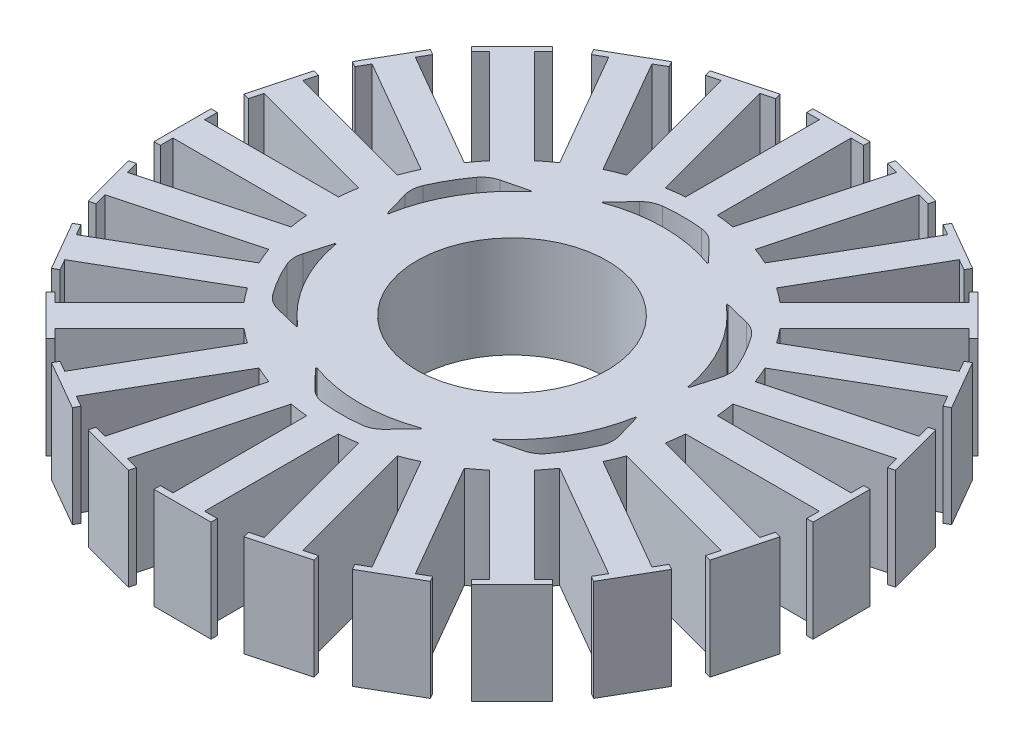
SolidWorks part; units mm, degrees
ref_plane "Front Plane" through (0, 0, 0) normal (0, 0, 1) x (1, 0, 0)
ref_plane "Top Plane" through (0, 0, 0) normal (0, 1, 0) x (1, 0, 0)
ref_plane "Right Plane" through (0, 0, 0) normal (1, 0, 0) x (0, 0, -1)
sketch "Sketch3" plane through (0, 0, 0) normal (0, 1, 0) x (1, 0, 0)
  line L0 (0, 0) -> (0, 19.6595) construction
  line L1 (-1.25, 25.5) -> (-1.25, 14.9478)
  line L2 (-1.25, 25.5) -> (-2.25, 25.5)
  line L3 (-2.25, 25.5) -> (-2.25, 26)
  line L4 (-2.25, 26) -> (2.25, 26)
  line L5 (2.25, 26) -> (2.25, 25.5)
  line L6 (2.25, 25.5) -> (1.25, 25.5)
  line L7 (1.25, 25.5) -> (1.25, 14.9478)
  line L8 (5.3925, 24.9546) -> (2.6614, 14.762)
  line L9 (7.8073, 24.3076) -> (5.0762, 14.115)
  line L10 (8.7732, 24.0488) -> (7.8073, 24.3076)
  line L11 (4.556, 25.6964) -> (8.9026, 24.5317)
  line L12 (5.3925, 24.9546) -> (4.4266, 25.2135)
  line L13 (4.4266, 25.2135) -> (4.556, 25.6964)
  line L14 (8.9026, 24.5317) -> (8.7732, 24.0488)
  line L15 (11.6675, 22.7086) -> (6.3914, 13.5702)
  line L16 (13.8325, 21.4586) -> (8.5564, 12.3202)
  line L17 (14.6986, 20.9586) -> (13.8325, 21.4586)
  line L18 (11.0514, 23.6417) -> (14.9486, 21.3917)
  line L19 (11.6675, 22.7086) -> (10.8014, 23.2086)
  line L20 (10.8014, 23.2086) -> (11.0514, 23.6417)
  line L21 (14.9486, 21.3917) -> (14.6986, 20.9586)
  line L22 (17.1473, 18.9151) -> (9.6858, 11.4536)
  line L23 (18.9151, 17.1473) -> (11.4536, 9.6858)
  line L24 (19.6222, 16.4402) -> (18.9151, 17.1473)
  line L25 (16.7938, 19.9758) -> (19.9758, 16.7938)
  line L26 (17.1473, 18.9151) -> (16.4402, 19.6222)
  line L27 (16.4402, 19.6222) -> (16.7938, 19.9758)
  line L28 (19.9758, 16.7938) -> (19.6222, 16.4402)
  line L29 (21.4586, 13.8325) -> (12.3202, 8.5564)
  line L30 (22.7086, 11.6675) -> (13.5702, 6.3914)
  line L31 (23.2086, 10.8014) -> (22.7086, 11.6675)
  line L32 (21.3917, 14.9486) -> (23.6417, 11.0514)
  line L33 (21.4586, 13.8325) -> (20.9586, 14.6986)
  line L34 (20.9586, 14.6986) -> (21.3917, 14.9486)
  line L35 (23.6417, 11.0514) -> (23.2086, 10.8014)
  line L36 (24.3076, 7.8073) -> (14.115, 5.0762)
  line L37 (24.9546, 5.3925) -> (14.762, 2.6614)
  line L38 (25.2135, 4.4266) -> (24.9546, 5.3925)
  line L39 (24.5317, 8.9026) -> (25.6964, 4.556)
  line L40 (24.3076, 7.8073) -> (24.0488, 8.7732)
  line L41 (24.0488, 8.7732) -> (24.5317, 8.9026)
  line L42 (25.6964, 4.556) -> (25.2135, 4.4266)
  line L43 (25.5, 1.25) -> (14.9478, 1.25)
  line L44 (25.5, -1.25) -> (14.9478, -1.25)
  line L45 (25.5, -2.25) -> (25.5, -1.25)
  line L46 (26, 2.25) -> (26, -2.25)
  line L47 (25.5, 1.25) -> (25.5, 2.25)
  line L48 (25.5, 2.25) -> (26, 2.25)
  line L49 (26, -2.25) -> (25.5, -2.25)
  line L50 (24.9546, -5.3925) -> (14.762, -2.6614)
  line L51 (24.3076, -7.8073) -> (14.115, -5.0762)
  line L52 (24.0488, -8.7732) -> (24.3076, -7.8073)
  line L53 (25.6964, -4.556) -> (24.5317, -8.9026)
  line L54 (24.9546, -5.3925) -> (25.2135, -4.4266)
  line L55 (25.2135, -4.4266) -> (25.6964, -4.556)
  line L56 (24.5317, -8.9026) -> (24.0488, -8.7732)
  line L57 (22.7086, -11.6675) -> (13.5702, -6.3914)
  line L58 (21.4586, -13.8325) -> (12.3202, -8.5564)
  line L59 (20.9586, -14.6986) -> (21.4586, -13.8325)
  line L60 (23.6417, -11.0514) -> (21.3917, -14.9486)
  line L61 (22.7086, -11.6675) -> (23.2086, -10.8014)
  line L62 (23.2086, -10.8014) -> (23.6417, -11.0514)
  line L63 (21.3917, -14.9486) -> (20.9586, -14.6986)
  line L64 (18.9151, -17.1473) -> (11.4536, -9.6858)
  line L65 (17.1473, -18.9151) -> (9.6858, -11.4536)
  line L66 (16.4402, -19.6222) -> (17.1473, -18.9151)
  line L67 (19.9758, -16.7938) -> (16.7938, -19.9758)
  line L68 (18.9151, -17.1473) -> (19.6222, -16.4402)
  line L69 (19.6222, -16.4402) -> (19.9758, -16.7938)
  line L70 (16.7938, -19.9758) -> (16.4402, -19.6222)
  line L71 (13.8325, -21.4586) -> (8.5564, -12.3202)
  line L72 (11.6675, -22.7086) -> (6.3914, -13.5702)
  line L73 (10.8014, -23.2086) -> (11.6675, -22.7086)
  line L74 (14.9486, -21.3917) -> (11.0514, -23.6417)
  line L75 (13.8325, -21.4586) -> (14.6986, -20.9586)
  line L76 (14.6986, -20.9586) -> (14.9486, -21.3917)
  line L77 (11.0514, -23.6417) -> (10.8014, -23.2086)
  line L78 (7.8073, -24.3076) -> (5.0762, -14.115)
  line L79 (5.3925, -24.9546) -> (2.6614, -14.762)
  line L80 (4.4266, -25.2135) -> (5.3925, -24.9546)
  line L81 (8.9026, -24.5317) -> (4.556, -25.6964)
  line L82 (7.8073, -24.3076) -> (8.7732, -24.0488)
  line L83 (8.7732, -24.0488) -> (8.9026, -24.5317)
  line L84 (4.556, -25.6964) -> (4.4266, -25.2135)
  line L85 (1.25, -25.5) -> (1.25, -14.9478)
  line L86 (-1.25, -25.5) -> (-1.25, -14.9478)
  line L87 (-2.25, -25.5) -> (-1.25, -25.5)
  line L88 (2.25, -26) -> (-2.25, -26)
  line L89 (1.25, -25.5) -> (2.25, -25.5)
  line L90 (2.25, -25.5) -> (2.25, -26)
  line L91 (-2.25, -26) -> (-2.25, -25.5)
  line L92 (-5.3925, -24.9546) -> (-2.6614, -14.762)
  line L93 (-7.8073, -24.3076) -> (-5.0762, -14.115)
  line L94 (-8.7732, -24.0488) -> (-7.8073, -24.3076)
  line L95 (-4.556, -25.6964) -> (-8.9026, -24.5317)
  line L96 (-5.3925, -24.9546) -> (-4.4266, -25.2135)
  line L97 (-4.4266, -25.2135) -> (-4.556, -25.6964)
  line L98 (-8.9026, -24.5317) -> (-8.7732, -24.0488)
  line L99 (-11.6675, -22.7086) -> (-6.3914, -13.5702)
  line L100 (-13.8325, -21.4586) -> (-8.5564, -12.3202)
  line L101 (-14.6986, -20.9586) -> (-13.8325, -21.4586)
  line L102 (-11.0514, -23.6417) -> (-14.9486, -21.3917)
  line L103 (-11.6675, -22.7086) -> (-10.8014, -23.2086)
  line L104 (-10.8014, -23.2086) -> (-11.0514, -23.6417)
  line L105 (-14.9486, -21.3917) -> (-14.6986, -20.9586)
  line L106 (-17.1473, -18.9151) -> (-9.6858, -11.4536)
  line L107 (-18.9151, -17.1473) -> (-11.4536, -9.6858)
  line L108 (-19.6222, -16.4402) -> (-18.9151, -17.1473)
  line L109 (-16.7938, -19.9758) -> (-19.9758, -16.7938)
  line L110 (-17.1473, -18.9151) -> (-16.4402, -19.6222)
  line L111 (-16.4402, -19.6222) -> (-16.7938, -19.9758)
  line L112 (-19.9758, -16.7938) -> (-19.6222, -16.4402)
  line L113 (-21.4586, -13.8325) -> (-12.3202, -8.5564)
  line L114 (-22.7086, -11.6675) -> (-13.5702, -6.3914)
  line L115 (-23.2086, -10.8014) -> (-22.7086, -11.6675)
  line L116 (-21.3917, -14.9486) -> (-23.6417, -11.0514)
  line L117 (-21.4586, -13.8325) -> (-20.9586, -14.6986)
  line L118 (-20.9586, -14.6986) -> (-21.3917, -14.9486)
  line L119 (-23.6417, -11.0514) -> (-23.2086, -10.8014)
  line L120 (-24.3076, -7.8073) -> (-14.115, -5.0762)
  line L121 (-24.9546, -5.3925) -> (-14.762, -2.6614)
  line L122 (-25.2135, -4.4266) -> (-24.9546, -5.3925)
  line L123 (-24.5317, -8.9026) -> (-25.6964, -4.556)
  line L124 (-24.3076, -7.8073) -> (-24.0488, -8.7732)
  line L125 (-24.0488, -8.7732) -> (-24.5317, -8.9026)
  line L126 (-25.6964, -4.556) -> (-25.2135, -4.4266)
  line L127 (-25.5, -1.25) -> (-14.9478, -1.25)
  line L128 (-25.5, 1.25) -> (-14.9478, 1.25)
  line L129 (-25.5, 2.25) -> (-25.5, 1.25)
  line L130 (-26, -2.25) -> (-26, 2.25)
  line L131 (-25.5, -1.25) -> (-25.5, -2.25)
  line L132 (-25.5, -2.25) -> (-26, -2.25)
  line L133 (-26, 2.25) -> (-25.5, 2.25)
  line L134 (-24.9546, 5.3925) -> (-14.762, 2.6614)
  line L135 (-24.3076, 7.8073) -> (-14.115, 5.0762)
  line L136 (-24.0488, 8.7732) -> (-24.3076, 7.8073)
  line L137 (-25.6964, 4.556) -> (-24.5317, 8.9026)
  line L138 (-24.9546, 5.3925) -> (-25.2135, 4.4266)
  line L139 (-25.2135, 4.4266) -> (-25.6964, 4.556)
  line L140 (-24.5317, 8.9026) -> (-24.0488, 8.7732)
  line L141 (-22.7086, 11.6675) -> (-13.5702, 6.3914)
  line L142 (-21.4586, 13.8325) -> (-12.3202, 8.5564)
  line L143 (-20.9586, 14.6986) -> (-21.4586, 13.8325)
  line L144 (-23.6417, 11.0514) -> (-21.3917, 14.9486)
  line L145 (-22.7086, 11.6675) -> (-23.2086, 10.8014)
  line L146 (-23.2086, 10.8014) -> (-23.6417, 11.0514)
  line L147 (-21.3917, 14.9486) -> (-20.9586, 14.6986)
  line L148 (-18.9151, 17.1473) -> (-11.4536, 9.6858)
  line L149 (-17.1473, 18.9151) -> (-9.6858, 11.4536)
  line L150 (-16.4402, 19.6222) -> (-17.1473, 18.9151)
  line L151 (-19.9758, 16.7938) -> (-16.7938, 19.9758)
  line L152 (-18.9151, 17.1473) -> (-19.6222, 16.4402)
  line L153 (-19.6222, 16.4402) -> (-19.9758, 16.7938)
  line L154 (-16.7938, 19.9758) -> (-16.4402, 19.6222)
  line L155 (-13.8325, 21.4586) -> (-8.5564, 12.3202)
  line L156 (-11.6675, 22.7086) -> (-6.3914, 13.5702)
  line L157 (-10.8014, 23.2086) -> (-11.6675, 22.7086)
  line L158 (-14.9486, 21.3917) -> (-11.0514, 23.6417)
  line L159 (-13.8325, 21.4586) -> (-14.6986, 20.9586)
  line L160 (-14.6986, 20.9586) -> (-14.9486, 21.3917)
  line L161 (-11.0514, 23.6417) -> (-10.8014, 23.2086)
  line L162 (-7.8073, 24.3076) -> (-5.0762, 14.115)
  line L163 (-5.3925, 24.9546) -> (-2.6614, 14.762)
  line L164 (-4.4266, 25.2135) -> (-5.3925, 24.9546)
  line L165 (-8.9026, 24.5317) -> (-4.556, 25.6964)
  line L166 (-7.8073, 24.3076) -> (-8.7732, 24.0488)
  line L167 (-8.7732, 24.0488) -> (-8.9026, 24.5317)
  line L168 (-4.556, 25.6964) -> (-4.4266, 25.2135)
  circle A0 centre (0, 0) radius 7.5
  arc A1 (-14.762, 2.6614) -> (-14.9478, 1.25) centre (0, 0) ccw
  arc A2 (-13.5702, 6.3914) -> (-14.115, 5.0762) centre (0, 0) ccw
  arc A3 (-11.4536, 9.6858) -> (-12.3202, 8.5564) centre (0, 0) ccw
  arc A4 (-8.5564, 12.3202) -> (-9.6858, 11.4536) centre (0, 0) ccw
  arc A5 (-5.0762, 14.115) -> (-6.3914, 13.5702) centre (0, 0) ccw
  arc A6 (-1.25, 14.9478) -> (-2.6614, 14.762) centre (0, 0) ccw
  arc A7 (2.6614, 14.762) -> (1.25, 14.9478) centre (0, 0) ccw
  arc A8 (6.3914, 13.5702) -> (5.0762, 14.115) centre (0, 0) ccw
  arc A9 (9.6858, 11.4536) -> (8.5564, 12.3202) centre (0, 0) ccw
  arc A10 (12.3202, 8.5564) -> (11.4536, 9.6858) centre (0, 0) ccw
  arc A11 (14.115, 5.0762) -> (13.5702, 6.3914) centre (0, 0) ccw
  arc A12 (14.9478, 1.25) -> (14.762, 2.6614) centre (0, 0) ccw
  arc A13 (14.762, -2.6614) -> (14.9478, -1.25) centre (0, 0) ccw
  arc A14 (13.5702, -6.3914) -> (14.115, -5.0762) centre (0, 0) ccw
  arc A15 (11.4536, -9.6858) -> (12.3202, -8.5564) centre (0, 0) ccw
  arc A16 (8.5564, -12.3202) -> (9.6858, -11.4536) centre (0, 0) ccw
  arc A17 (5.0762, -14.115) -> (6.3914, -13.5702) centre (0, 0) ccw
  arc A18 (1.25, -14.9478) -> (2.6614, -14.762) centre (0, 0) ccw
  arc A19 (-2.6614, -14.762) -> (-1.25, -14.9478) centre (0, 0) ccw
  arc A20 (-6.3914, -13.5702) -> (-5.0762, -14.115) centre (0, 0) ccw
  arc A21 (-9.6858, -11.4536) -> (-8.5564, -12.3202) centre (0, 0) ccw
  arc A22 (-12.3202, -8.5564) -> (-11.4536, -9.6858) centre (0, 0) ccw
  arc A23 (-14.115, -5.0762) -> (-13.5702, -6.3914) centre (0, 0) ccw
  arc A24 (-14.9478, -1.25) -> (-14.762, -2.6614) centre (0, 0) ccw
  point P9 (0, 26)
  point P201 (0, 0)
  dimension "D1" = 15
  dimension "D3" = 30
  dimension "D2" = 4.5
  dimension "D4" = 0.5
  dimension "D5" = 0.5
  dimension "D6" = 2.5
  dimension "D7" = 26
  dimension "D8" = 24
extrude "Boss-Extrude1" add sketch "Sketch3" along normal blind 8
sketch "Sketch4" plane through (0, 8, 0) normal (0, 1, 0) x (1, 0, 0)
  line L0 (-2.6614, 14.762) -> (-1.0542, 8.764) construction
  line L1 (2.6614, 14.762) -> (4.7776, 22.6598) construction
  line L2 (2.7481, 12.8126) -> (4.1439, 11.3629)
  line L3 (-5.0762, 14.115) -> (-6.077, 17.8501) construction
  line L4 (9.722, 8.7862) -> (7.7686, 9.2702)
  line L5 (5.0762, 14.115) -> (6.0658, 17.8082) construction
  line L6 (12.4701, 4.0263) -> (11.9125, 2.0927)
  line L7 (-2.7481, 12.8126) -> (-4.1439, 11.3629)
  line L8 (12.4701, -4.0263) -> (11.9125, -2.0927)
  line L9 (9.722, -8.7862) -> (7.7686, -9.2702)
  line L10 (2.7481, -12.8126) -> (4.1439, -11.3629)
  line L11 (-2.7481, -12.8126) -> (-4.1439, -11.3629)
  line L12 (-9.722, -8.7862) -> (-7.7686, -9.2702)
  line L13 (-12.4701, -4.0263) -> (-11.9125, -2.0927)
  line L14 (-12.4701, 4.0263) -> (-11.9125, 2.0927)
  line L15 (-9.722, 8.7862) -> (-7.7686, 9.2702)
  arc A0 (-4.6865, -12.6605) -> (4.6865, -12.6605) centre (0, 0) ccw construction
  arc A1 (-8.5564, 12.3202) -> (-9.6858, 11.4536) centre (0, 0) ccw construction
  arc A2 (-4.2963, -11.2045) -> (4.2963, -11.2045) centre (0, 0) ccw construction
  circle A3 centre (0, 0) radius 13.5 construction
  circle A4 centre (0, 0) radius 12 construction
  arc A5 (4.0908, 11.2812) -> (-4.0908, 11.2812) centre (0, 0) ccw
  arc A6 (1.5347, 13.4125) -> (-1.5347, 13.4125) centre (0, 0) ccw
  arc A7 (-1.5347, 13.4125) -> (-2.7481, 12.8126) centre (-1.3074, 11.4254) ccw
  arc A8 (1.5347, 13.4125) -> (2.7481, 12.8126) centre (1.3074, 11.4254) cw
  arc A9 (4.1439, 11.3629) -> (4.0908, 11.2812) centre (4.1079, 11.3282) cw
  arc A10 (-4.0908, 11.2812) -> (-4.1439, 11.3629) centre (-4.1079, 11.3282) cw
  arc A11 (7.7244, 9.1834) -> (7.7686, 9.2702) centre (7.7566, 9.2216) cw
  arc A12 (10.8482, 8.0354) -> (9.722, 8.7862) centre (9.241, 6.8449) ccw
  arc A13 (11.8152, 2.0978) -> (7.7244, 9.1834) centre (0, 0) ccw
  arc A14 (11.9125, 2.0927) -> (11.8152, 2.0978) centre (11.8644, 2.1066) cw
  arc A15 (12.3829, 5.3771) -> (12.4701, 4.0263) centre (10.5484, 4.5805) cw
  arc A16 (12.3829, 5.3771) -> (10.8482, 8.0354) centre (0, 0) ccw
  arc A17 (11.8152, -2.0978) -> (11.9125, -2.0927) centre (11.8644, -2.1066) cw
  arc A18 (12.3829, -5.3771) -> (12.4701, -4.0263) centre (10.5484, -4.5805) ccw
  arc A19 (7.7244, -9.1834) -> (11.8152, -2.0978) centre (0, 0) ccw
  arc A20 (7.7686, -9.2702) -> (7.7244, -9.1834) centre (7.7566, -9.2216) cw
  arc A21 (10.8482, -8.0354) -> (9.722, -8.7862) centre (9.241, -6.8449) cw
  arc A22 (10.8482, -8.0354) -> (12.3829, -5.3771) centre (0, 0) ccw
  arc A23 (4.0908, -11.2812) -> (4.1439, -11.3629) centre (4.1079, -11.3282) cw
  arc A24 (1.5347, -13.4125) -> (2.7481, -12.8126) centre (1.3074, -11.4254) ccw
  arc A25 (-4.0908, -11.2812) -> (4.0908, -11.2812) centre (0, 0) ccw
  arc A26 (-4.1439, -11.3629) -> (-4.0908, -11.2812) centre (-4.1079, -11.3282) cw
  arc A27 (-1.5347, -13.4125) -> (-2.7481, -12.8126) centre (-1.3074, -11.4254) cw
  arc A28 (-1.5347, -13.4125) -> (1.5347, -13.4125) centre (0, 0) ccw
  arc A29 (-7.7244, -9.1834) -> (-7.7686, -9.2702) centre (-7.7566, -9.2216) cw
  arc A30 (-10.8482, -8.0354) -> (-9.722, -8.7862) centre (-9.241, -6.8449) ccw
  arc A31 (-11.8152, -2.0978) -> (-7.7244, -9.1834) centre (0, 0) ccw
  arc A32 (-11.9125, -2.0927) -> (-11.8152, -2.0978) centre (-11.8644, -2.1066) cw
  arc A33 (-12.3829, -5.3771) -> (-12.4701, -4.0263) centre (-10.5484, -4.5805) cw
  arc A34 (-12.3829, -5.3771) -> (-10.8482, -8.0354) centre (0, 0) ccw
  arc A35 (-11.8152, 2.0978) -> (-11.9125, 2.0927) centre (-11.8644, 2.1066) cw
  arc A36 (-12.3829, 5.3771) -> (-12.4701, 4.0263) centre (-10.5484, 4.5805) ccw
  arc A37 (-7.7244, 9.1834) -> (-11.8152, 2.0978) centre (0, 0) ccw
  arc A38 (-7.7686, 9.2702) -> (-7.7244, 9.1834) centre (-7.7566, 9.2216) cw
  arc A39 (-10.8482, 8.0354) -> (-9.722, 8.7862) centre (-9.241, 6.8449) cw
  arc A40 (-10.8482, 8.0354) -> (-12.3829, 5.3771) centre (0, 0) ccw
  point P27 (-2.2716, 13.3075)
  point P30 (2.2716, 13.3075)
  point P33 (4.2963, 11.2045)
  point P36 (-4.2963, 11.2045)
  point P98 (0, 0)
  dimension "D1" = 1.5
  dimension "D3" = 2
  dimension "D4" = 0.05
  dimension "D2" = 1.5
  dimension "D5" = 6
extrude "Cut-Extrude1" cut sketch "Sketch4" against normal blind 8
